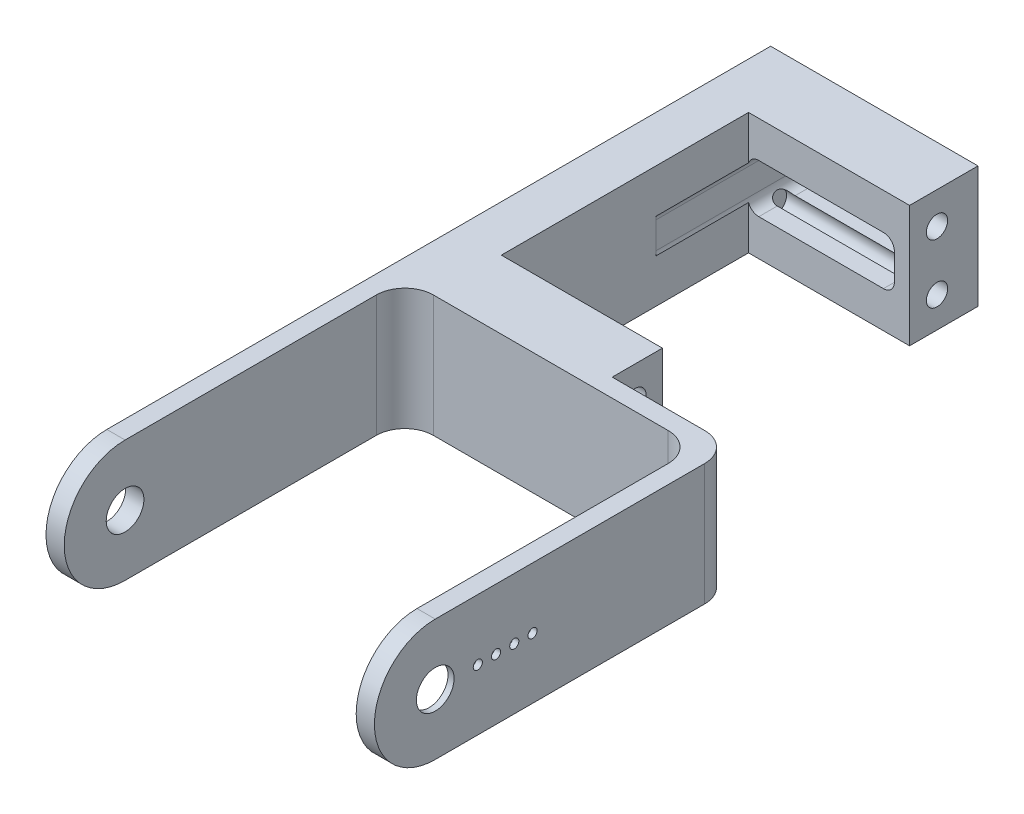
SolidWorks part; units mm, degrees
ref_plane "Vorne" through (0, 0, 0) normal (0, 0, 1) x (1, 0, 0)
ref_plane "Oben" through (0, 0, 0) normal (0, 1, 0) x (1, 0, 0)
ref_plane "Rechts" through (0, 0, 0) normal (1, 0, 0) x (0, 0, -1)
sketch "Skizze1" plane through (0, 0, 0) normal (0, 1, 0) x (1, 0, 0)
  line L1 (0, 0) -> (54, 0)
  line L2 (0, 0) -> (0, 59)
  line L3 (0, 59) -> (49.3, 59)
  line L4 (54, 0) -> (54, 54.3)
  line L5 (51, 0) -> (3, 0)
  line L6 (51, 0) -> (51, 51.3)
  line L7 (46.3, 56) -> (7.7, 56)
  line L8 (3, 0) -> (3, 51.3)
  arc A0 (51, 51.3) -> (46.3, 56) centre (46.3, 51.3) ccw
  arc A1 (7.7, 56) -> (3, 51.3) centre (7.7, 51.3) ccw
  arc A2 (49.3, 59) -> (54, 54.3) centre (49.3, 54.3) cw
  dimension "D6" = 4.7
  dimension "D7" = 4.7
  dimension "D1" = 59
  dimension "D2" = 54
  dimension "D3" = 3
  dimension "D4" = 3
  dimension "D5" = 3
extrude "Aufsatz-Linear austragen1" add sketch "Skizze1" along normal blind 20 contours L1 L8 L7 L6 L4 L3 L2
sketch "Skizze2" plane through (54, 0, 0) normal (1, 0, 0) x (0, 0, -1)
  line L0 (0, 20) -> (0, 0) construction
  line L1 (10, 20) -> (0, 20)
  line L2 (0, 20) -> (0, 0)
  line L3 (0, 0) -> (10, 0)
  arc A0 (10, 20) -> (10, 0) centre (10, 10) ccw
  line M1 (0, 0) -> (54.3, 0)
  line M3 (54.3, 20) -> (0, 20)
  line M4 (0, 20) -> (0, 0)
  dimension "D1" = 10
extrude "Schnitt-Linear austragen1" cut sketch "Skizze2" against normal blind 79.7 contours A0 M3 M4 | A0 L2 M1
sketch "Skizze3" plane through (54, 0, 0) normal (1, 0, 0) x (0, 0, -1)
  circle A0 centre (10, 10) radius 3.1
  dimension "D1" = 6.2
extrude "Schnitt-Linear austragen2" cut sketch "Skizze3" against normal blind 94.75
sketch "Skizze4" plane through (51, 0, 0) normal (-1, 0, 0) x (0, 0, 1)
  line L0 (-27.5, 12.5) -> (-14.8073, 14.375)
  line L1 (-27.5, 7.5) -> (-14.8073, 5.625)
  arc A0 (-14.8073, 5.625) -> (-14.8073, 14.375) centre (-10, 10) ccw
  arc A1 (-27.5, 12.5) -> (-27.5, 7.5) centre (-27.5, 10) ccw
  arc A2 (-10, 0) -> (-10, 20) centre (-10, 10) ccw construction
  dimension "D1" = 0
extrude "Schnitt-Linear austragen3" cut sketch "Skizze4" against normal blind 2
sketch "Skizze5" plane through (53, 0, 0) normal (-1, 0, 0) x (0, 0, 1)
  circle A0 centre (-25.9955, 10) radius 0.75
  circle A1 centre (-22.9955, 10) radius 0.75
  circle A2 centre (-19.9955, 10) radius 0.75
  circle A3 centre (-16.9955, 10) radius 0.75
  circle A4 centre (-10, 10) radius 3.1 construction
  dimension "D1" = 3
  dimension "D2" = 3
  dimension "D3" = 3
  dimension "D4" = 6.9955
  dimension "D5" = 0
extrude "Schnitt-Linear austragen4" cut sketch "Skizze5" against normal blind 2
sketch "Skizze6" plane through (0, 0, 0) normal (0, -1, 0) x (1, 0, 0)
  line L2 (34.094, -59.2569) -> (34.094, -67.2569)
  line L3 (34.094, -67.2569) -> (0, -67.2569)
  line L4 (0, -59.2569) -> (0, -67.2569)
  line L6 (0, -59.2569) -> (0, -57.8944)
  line L7 (0, -57.8944) -> (34.094, -57.8944)
  line L8 (34.094, -59.2569) -> (34.094, -57.8944)
extrude "Aufsatz-Linear austragen2" add sketch "Skizze6" against normal blind 20
sketch "Skizze7" plane through (0, 0, 0) normal (0, -1, 0) x (1, 0, 0)
  line L1 (0, -67.2569) -> (7.6117, -67.2569)
  line L2 (0, -67.2569) -> (0, -119.1478)
  line L3 (0, -119.1478) -> (7.6117, -119.1478)
  line L4 (7.6117, -67.2569) -> (7.6117, -119.1478)
extrude "Aufsatz-Linear austragen3" add sketch "Skizze7" against normal blind 20
sketch "Skizze8" plane through (7.6117, 0, 0) normal (1, 0, 0) x (0, 0, -1)
  line L1 (119.1478, 20) -> (107.8992, 20)
  line L2 (119.1478, 20) -> (119.1478, 0)
  line L3 (119.1478, 0) -> (107.8992, 0)
  line L4 (107.8992, 20) -> (107.8992, 0)
  line L5 (119.1478, 0) -> (67.2569, 0) construction
  dimension "D1" = 0
extrude "Aufsatz-Linear austragen4" add sketch "Skizze8" along normal blind 26.48
sketch "Skizze9" plane through (0, 0, -119.1478) normal (0, 0, -1) x (-1, 0, 0)
  line L0 (0, 20) -> (-34.0917, 20) construction
  line L1 (-9.3, 14) -> (-29.794, 14)
  line L2 (-7.5, 12.2) -> (-7.5, 7.8)
  line L3 (-9.3, 6) -> (-29.794, 6)
  line L4 (-31.594, 12.2) -> (-31.594, 7.8)
  line L5 (0, 0) -> (-34.0917, 0) construction
  line L6 (-34.094, 18.9) -> (-34.094, 0.9) construction
  line L7 (0, 20) -> (0, 0) construction
  arc A0 (-9.3, 14) -> (-7.5, 12.2) centre (-9.3, 12.2) cw
  arc A1 (-7.5, 7.8) -> (-9.3, 6) centre (-9.3, 7.8) cw
  arc A2 (-29.794, 6) -> (-31.594, 7.8) centre (-29.794, 7.8) cw
  arc A3 (-29.794, 14) -> (-31.594, 12.2) centre (-29.794, 12.2) ccw
  dimension "D5" = 1.8
  dimension "D1" = 6
  dimension "D2" = 6
  dimension "D3" = 2.5
  dimension "D4" = 7.5
extrude "Schnitt-Linear austragen5" cut sketch "Skizze9" against normal blind 26.48
sketch "Skizze10" plane through (34.0917, 0, 0) normal (1, 0, 0) x (0, 0, -1)
  circle A0 centre (62.8069, 14.75) radius 1.75
  circle A1 centre (62.8069, 5.05) radius 1.75
  circle A2 centre (112.4069, 5.05) radius 1.75
  circle A3 centre (112.4069, 14.75) radius 1.75
  dimension "D1" = 3.5
  dimension "D2" = 3.5
  dimension "D3" = 3.5
  dimension "D4" = 3.5
extrude "Schnitt-Linear austragen6" cut sketch "Skizze10" against normal blind 26.48 and the other way blind 6
sketch "Skizze11" plane through (0, 0, 0) normal (-1, 0, 0) x (0, 0, 1)
  circle A0 centre (-99.4569, 9.9) radius 3
  dimension "D1" = 6
extrude "Aufsatz-Linear austragen5" add sketch "Skizze11" along normal blind 6
